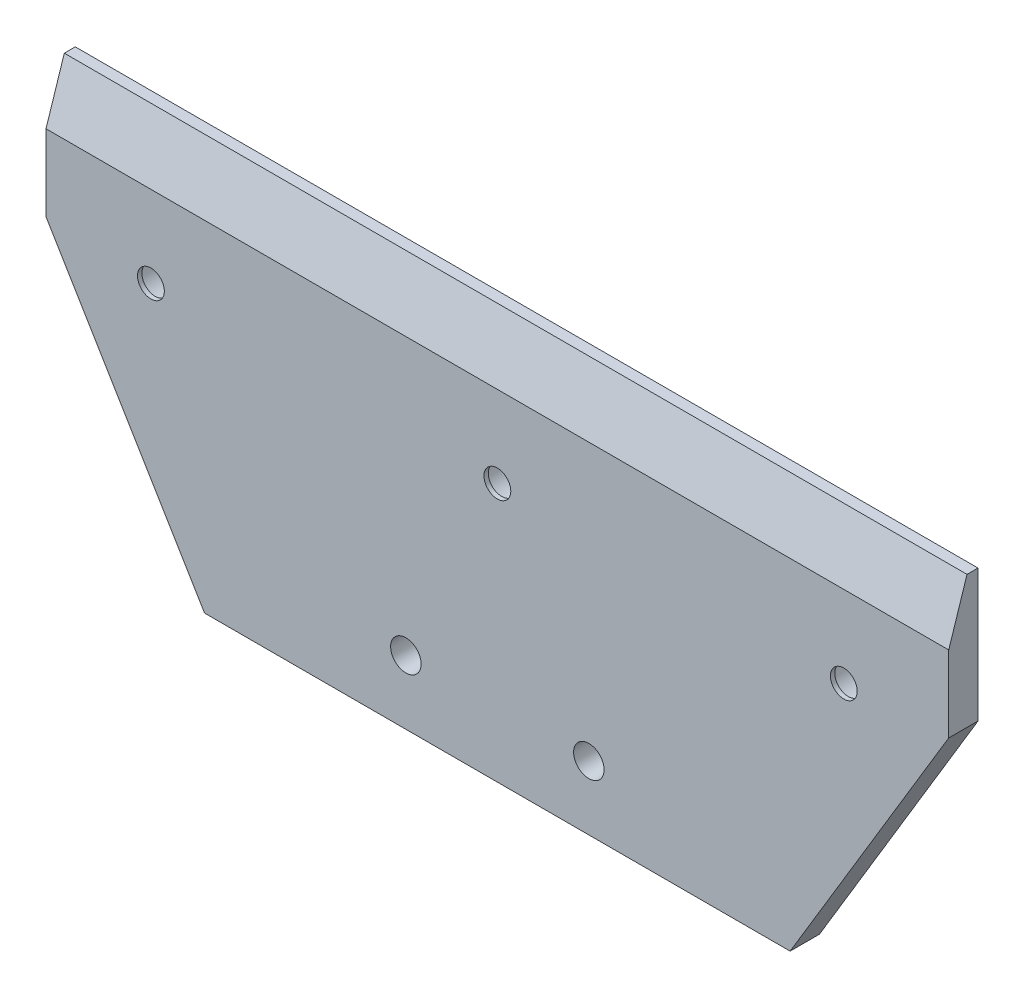
SolidWorks part; units mm, degrees
material "AISI 316 Stainless Steel Sheet (SS)"
ref_plane "Спереди" through (0, 0, 0) normal (0, 0, 1) x (1, 0, 0)
ref_plane "Сверху" through (0, 0, 0) normal (0, 1, 0) x (1, 0, 0)
ref_plane "Справа" through (0, 0, 0) normal (1, 0, 0) x (0, 0, -1)
sketch "Sketch1" plane through (0, 0, 0) normal (0, 0, 1) x (1, 0, 0)
  line L0 (-24, 0) -> (24, 0)
  line L1 (24, 0) -> (37, 21.6356)
  line L2 (37, 21.6356) -> (37, 32.5)
  line L3 (37, 32.5) -> (-37, 32.5)
  line L4 (-37, 32.5) -> (-37, 21.6356)
  line L5 (-37, 21.6356) -> (-24, 0)
  dimension "D1" = 74
  dimension "D2" = 48
  dimension "D3" = 32.5
  dimension "D4" = 121
extrude "Boss-Extrude1" add sketch "Sketch1" along normal mid plane 2.4
sketch "Sketch2" plane through (37, 0, 0) normal (1, 0, 0) x (0, 0, -1)
  line L0 (-1.2, 27.8835) -> (0.3, 32.5)
  line L1 (-1.2, 21.6356) -> (-1.2, 32.5) construction
  line L2 (-1.2, 32.5) -> (1.2, 32.5) construction
  line L3 (-1.2, 27.8835) -> (-1.2, 32.5)
  line L4 (-1.2, 32.5) -> (0.3, 32.5)
  line L5 (1.2, 21.6356) -> (1.2, 32.5) construction
  dimension "D1" = 162
  dimension "D2" = 0.9
extrude "Cut-Extrude1" cut sketch "Sketch2" against normal through all
sketch "Sketch3" plane through (0, 0, 1.2) normal (0, 0, 1) x (1, 0, 0)
  line L0 (-24, 0) -> (24, 0) construction
  point P0 (-7.5, 5.25)
  point P1 (7.5, 5.25)
  dimension "D1" = 5.25
  dimension "D2" = 15
  dimension "D3" = 7.5
hole_wizard "Ø2.5 (2.5) Diameter Hole1" positions "Sketch4" profile "Sketch5" hole size "Ø2.5" standard "ISO"
sketch "Sketch4" plane through (0, 0, 1.2) normal (0, 0, 1) x (1, 0, 0)
  point P0 (-7.5, 5.25)
  point P3 (7.5, 5.25)
sketch "Sketch5" plane through (-7.5, 5.25, 1.2) normal (1, 0, 0) x (0, -1, 0)
  line L0 (0, 0) -> (0, 10.7511)
  line L1 (0, 10.7511) -> (1.25, 10)
  line L2 (1.25, 10) -> (1.25, 0)
  line L5 (1.25, 0) -> (0, 0)
  line L10 (0, 10.7511) -> (-1.25, 10) construction
  line L11 (0, -6.35) -> (0, 107.95) construction
  dimension "Hole Dia." = 2.5
  dimension "Hole Depth" = 10
  dimension "Drill Angle" = 118
sketch "Sketch6" plane through (0, 0, 1.2) normal (0, 0, 1) x (1, 0, 0)
  line L0 (-24, 0) -> (24, 0) construction
  point P0 (0, 21.2)
  point P1 (-28.4, 21.2)
  point P2 (28.4, 21.2)
  dimension "D1" = 56.8
  dimension "D2" = 28.4
  dimension "D3" = 21.2
sketch "Sketch7" plane through (0, 0, -1.2) normal (0, 0, -1) x (-1, 0, 0)
  line L6 (24, 0) -> (37, 21.6356)
  line L7 (37, 21.6356) -> (37, 32.5)
  line L8 (37, 32.5) -> (-37, 32.5)
  line L9 (-37, 32.5) -> (-37, 21.6356)
  line L10 (-37, 21.6356) -> (-24, 0)
  line L11 (-24, 0) -> (24, 0)
  line L12 (24, 0) -> (37, 21.6356)
  line L13 (37, 21.6356) -> (37, 32.5)
  line L14 (37, 32.5) -> (-37, 32.5)
  line L15 (-37, 32.5) -> (-37, 21.6356)
  line L16 (-37, 21.6356) -> (-24, 0)
  line L17 (-24, 0) -> (24, 0)
  point P2 (-28.4, 21.2)
  point P4 (0, 21.2)
  point P6 (28.4, 21.2)
  dimension "D1" = 0
hole_wizard "HoleWzd1" positions "3DSketch3" profile "Sketch10" legacy end condition up to next
sketch3d "3DSketch3"
  point P0 (28.4, 21.2, -1.2)
  point P3 (0, 21.2, -1.2)
  point P6 (-28.4, 21.2, -1.2)
sketch "Sketch10" plane through (28.4, 21.2, -1.2) normal (1, 0, 0) x (0, 1, 0)
  line L0 (0, 0) -> (0, 2.4)
  line L1 (0, 2.4) -> (1.1, 2.4)
  line L2 (1.1, 2.4) -> (1.1, 2.0408)
  line L3 (1.1, 2.0408) -> (2, 1.5)
  line L4 (2, 1.5) -> (2, 0)
  line L5 (2, 0) -> (0, 0)
  line L6 (0, -6.13) -> (0, 109.2824) construction
  line L7 (-1.1, 2.0408) -> (-2, 1.5) construction
  line L8 (0, 2.4) -> (-1.1, 2.4) construction
  dimension "Diameter" = 2.2
  dimension "Depth" = 2.4
  dimension "C-Drill Diameter" = 4
  dimension "C-Drill Depth" = 1.5
  dimension "C-Drill Angle" = 118
equation "\"D3@Sketch3\"=15/2"
